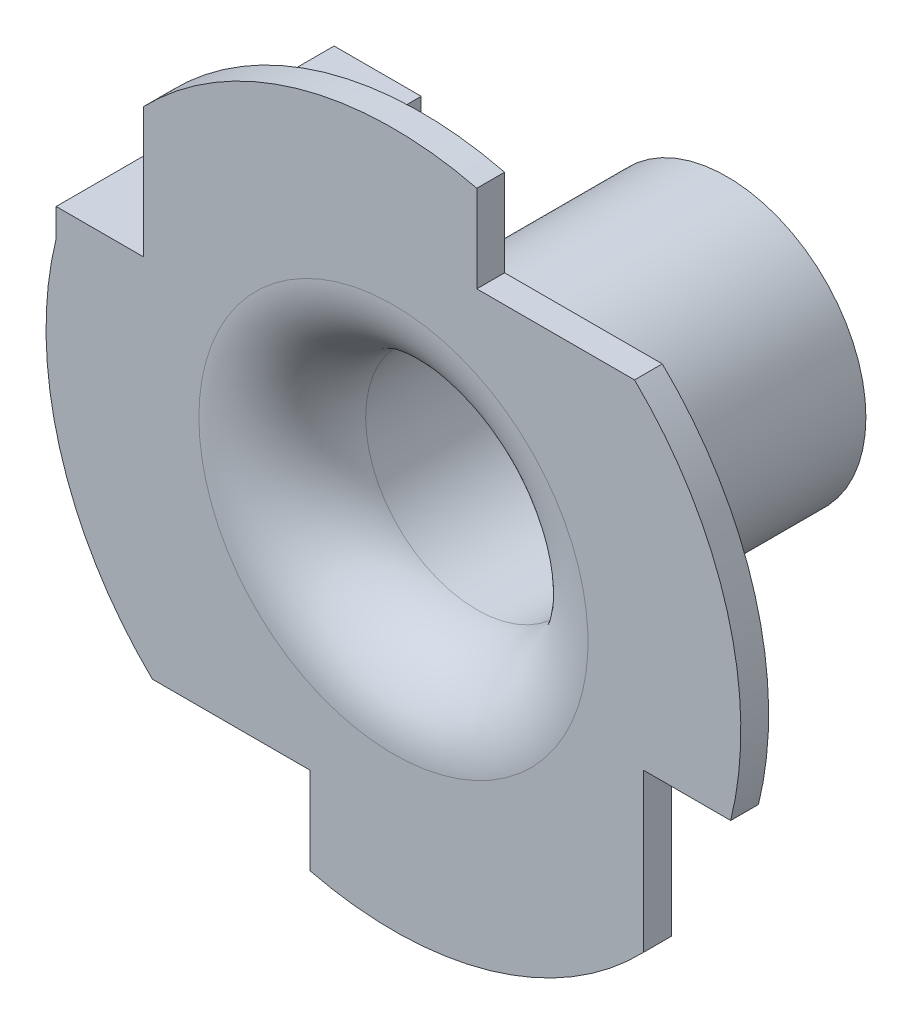
SolidWorks part; units mm, degrees
ref_plane "Front Plane" through (0, 0, 0) normal (0, 0, 1) x (1, 0, 0)
ref_plane "Top Plane" through (0, 0, 0) normal (0, 1, 0) x (1, 0, 0)
ref_plane "Right Plane" through (0, 0, 0) normal (1, 0, 0) x (0, 0, -1)
sketch "Sketch2" plane through (0, 0, 0) normal (0, 1, 0) x (1, 0, 0)
  line L0 (0, 90.4084) -> (0, 0) construction
  line L7 (4, 11) -> (4, 2)
  line L8 (7, -1) -> (12.5, -1)
  line L9 (5, 11) -> (5, 2)
  line L10 (7, 0) -> (12.5, 0)
  line L11 (4, 11) -> (5, 11)
  line L12 (12.5, 0) -> (12.5, -1)
  arc A2 (4, 2) -> (7, -1) centre (7, 2) ccw
  arc A3 (5, 2) -> (7, 0) centre (7, 2) ccw
  dimension "D3" = 2
  dimension "D1" = 3
  dimension "D2" = 1
  dimension "D4" = 12
  dimension "D5" = 1
  dimension "D6" = 25
  dimension "D7" = 8
revolve "Revolve1" add sketch "Sketch2" angle 360 about L0
sketch "Sketch3" plane through (0, 0, 0) normal (0, 0, -1) x (-1, 0, 0)
  line L0 (0, 0) -> (0, 13.3641) construction
  line L1 (0, 0) -> (16.9771, 0) construction
  line L2 (9, 8.6747) -> (9, 3)
  line L3 (9, 3) -> (12.1347, 3)
  line L4 (8.6747, -9) -> (3, -9)
  line L5 (3, -9) -> (3, -12.1347)
  line L6 (-9, -8.6747) -> (-9, -3)
  line L7 (-9, -3) -> (-12.1347, -3)
  line L8 (-8.6747, 9) -> (-3, 9)
  line L9 (-3, 9) -> (-3, 12.1347)
  circle A0 centre (0, 0) radius 12.5 construction
  arc A1 (12.1347, 3) -> (9, 8.6747) centre (0, 0) ccw
  arc A2 (3, -12.1347) -> (8.6747, -9) centre (0, 0) ccw
  arc A3 (-12.1347, -3) -> (-9, -8.6747) centre (0, 0) ccw
  arc A4 (-3, 12.1347) -> (-8.6747, 9) centre (0, 0) ccw
  point P21 (0, 0)
  dimension "D1" = 9
  dimension "D2" = 3
  dimension "D3" = 4
extrude "Cut-Extrude1" cut sketch "Sketch3" against normal blind 10
sketch "Sketch4" plane through (0, 0, 0) normal (0, 0, -1) x (-1, 0, 0)
  line L1 (9, 3) -> (12.1347, 3)
  line L2 (9, 3) -> (9, 4)
  line L3 (9, 4) -> (12.1347, 4)
  line L4 (12.1347, 3) -> (12.1347, 4)
  point P5 (12.1347, 3)
  dimension "D1" = 1
extrude "Boss-Extrude1" add sketch "Sketch4" along normal blind 9 and the other way blind 1 contours L4 L3 L2 L1
sketch "Sketch6" plane through (0, 3, 0) normal (0, -1, 0) x (1, 0, 0)
  arc A0 (-12.1347, 0) -> (-9, -9) centre (2.3527, 0) ccw
  point P3 (0, 0)
  point P6 (0, -0.8239)
  point P7 (0, 0)
